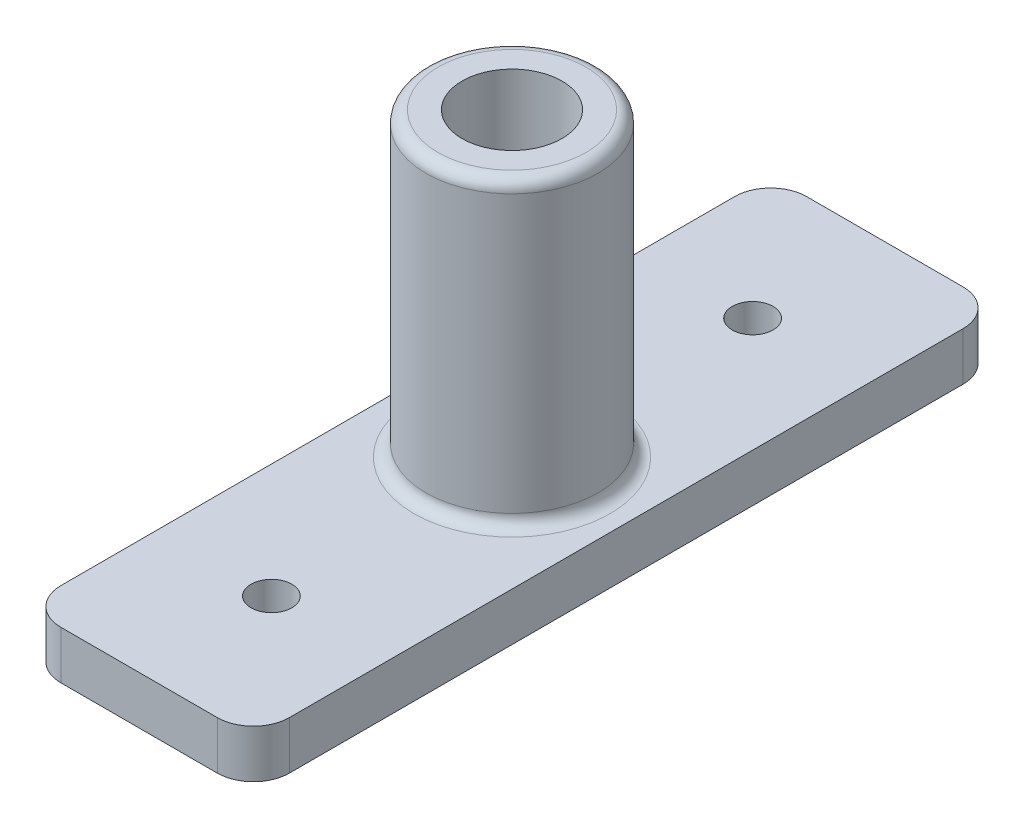
SolidWorks part; units mm, degrees
ref_plane "前视基准面" through (0, 0, 0) normal (0, 0, 1) x (1, 0, 0)
ref_plane "上视基准面" through (0, 0, 0) normal (0, 1, 0) x (1, 0, 0)
ref_plane "右视基准面" through (0, 0, 0) normal (1, 0, 0) x (0, 0, -1)
other "Configuration Table"
sketch "草图2" plane through (0, 0, 0) normal (0, 1, 0) x (1, 0, 0)
  line L0 (0, 35.3865) -> (0, -47.0335) construction
  line L1 (9.5, -31) -> (-9.5, -31)
  line L2 (9.5, -31) -> (9.5, 31)
  line L3 (9.5, 31) -> (-9.5, 31)
  line L4 (-9.5, -31) -> (-9.5, 31)
  line L5 (9.5, -31) -> (-9.5, 31) construction
  line L6 (9.5, 31) -> (-9.5, -31) construction
  line L7 (-22.0951, 0) -> (29.6194, 0) construction
  circle A0 centre (0, 20) radius 1.7
  circle A1 centre (0, -20) radius 1.7
  point P0 (0, 0)
  dimension "D5" = 3.4
  dimension "D1" = 62
  dimension "D2" = 19
  dimension "D3" = 40
  dimension "D4" = 20
extrude "凸台-拉伸1" add sketch "草图2" along normal blind 4
sketch "草图3" plane through (0, 4, 0) normal (0, 1, 0) x (1, 0, 0)
  circle A0 centre (0, 0) radius 7.15
  circle A1 centre (0, 0) radius 4.15
  dimension "D1" = 14.3
  dimension "D2" = 8.3
extrude "凸台-拉伸2" add sketch "草图3" along normal blind 25
fillet "圆角1" radius 3 4 edges at (9.5, 2, -31) (9.5, 2, 31) (-9.5, 2, -31) (-9.5, 2, 31)
fillet "圆角2" radius 1 2 edges at (0, 29, 7.15) (0, 4, 7.15)
